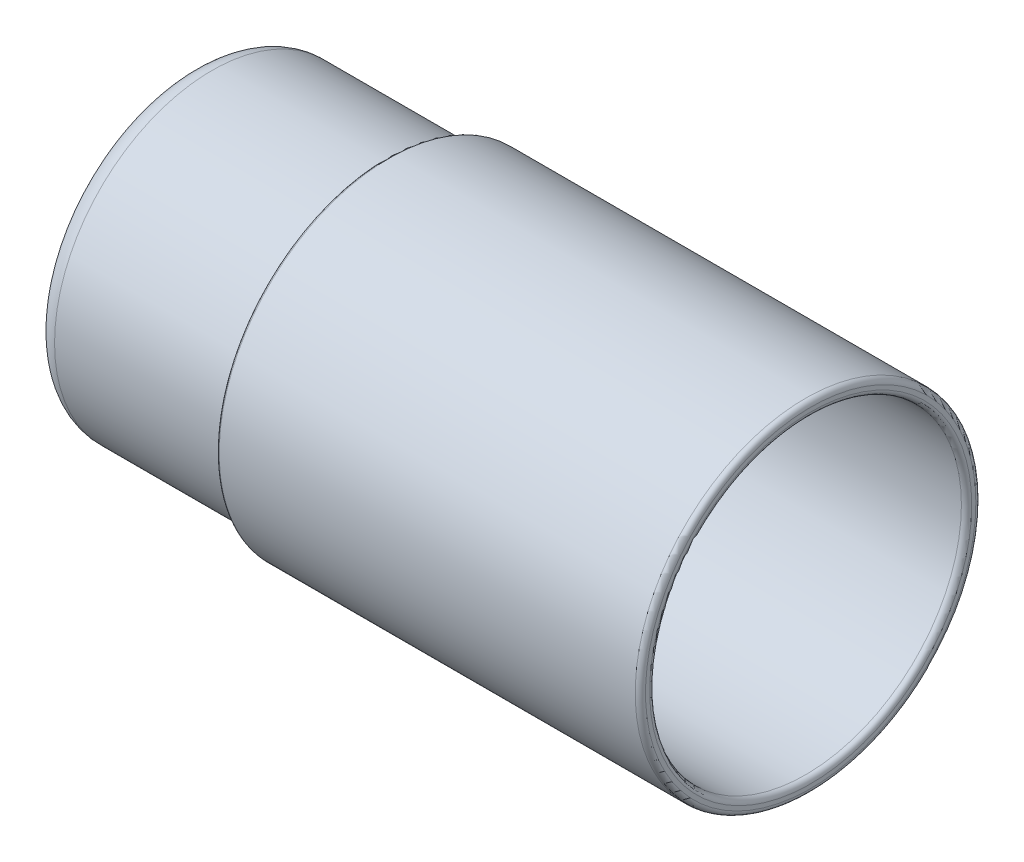
SolidWorks part; units mm, degrees
ref_plane "Front Plane" through (0, 0, 0) normal (0, 0, 1) x (1, 0, 0)
ref_plane "Top Plane" through (0, 0, 0) normal (0, 1, 0) x (1, 0, 0)
ref_plane "Right Plane" through (0, 0, 0) normal (1, 0, 0) x (0, 0, -1)
sketch "Sketch1" plane through (0, 0, 0) normal (0, 1, 0) x (1, 0, 0)
  line L0 (0, 0) -> (0, 13.25)
  line L1 (2, 15.25) -> (19, 15.25)
  line L2 (19, 15.25) -> (19, 16.3)
  line L3 (19.2, 16.5) -> (59.5, 16.5)
  line L4 (60, 16) -> (60, 15.6)
  line L5 (30, 0) -> (0, 0)
  line L6 (30, 0) -> (-23.9956, 0) construction
  line L7 (59.5, 15.1) -> (32, 15.1)
  line L8 (30, 13.1) -> (30, 0)
  arc A0 (32, 15.1) -> (30, 13.1) centre (32, 13.1) ccw
  arc A1 (0, 13.25) -> (2, 15.25) centre (2, 13.25) cw
  arc A2 (19, 16.3) -> (19.2, 16.5) centre (19.2, 16.3) cw
  arc A3 (59.5, 16.5) -> (60, 16) centre (59.5, 16) cw
  arc A4 (59.5, 15.1) -> (60, 15.6) centre (59.5, 15.6) ccw
  point P18 (0, 15.25)
  point P21 (19, 16.5)
  point P24 (60, 16.5)
  dimension "D4" = 2
  dimension "D8" = 2
  dimension "D9" = 0.2
  dimension "D10" = 0.5
  dimension "D1" = 30.5
  dimension "D2" = 60
  dimension "D3" = 30.2
  dimension "D5" = 30
  dimension "D6" = 19
  dimension "D7" = 33
revolve "Revolve1" add sketch "Sketch1" angle 360 about L6
